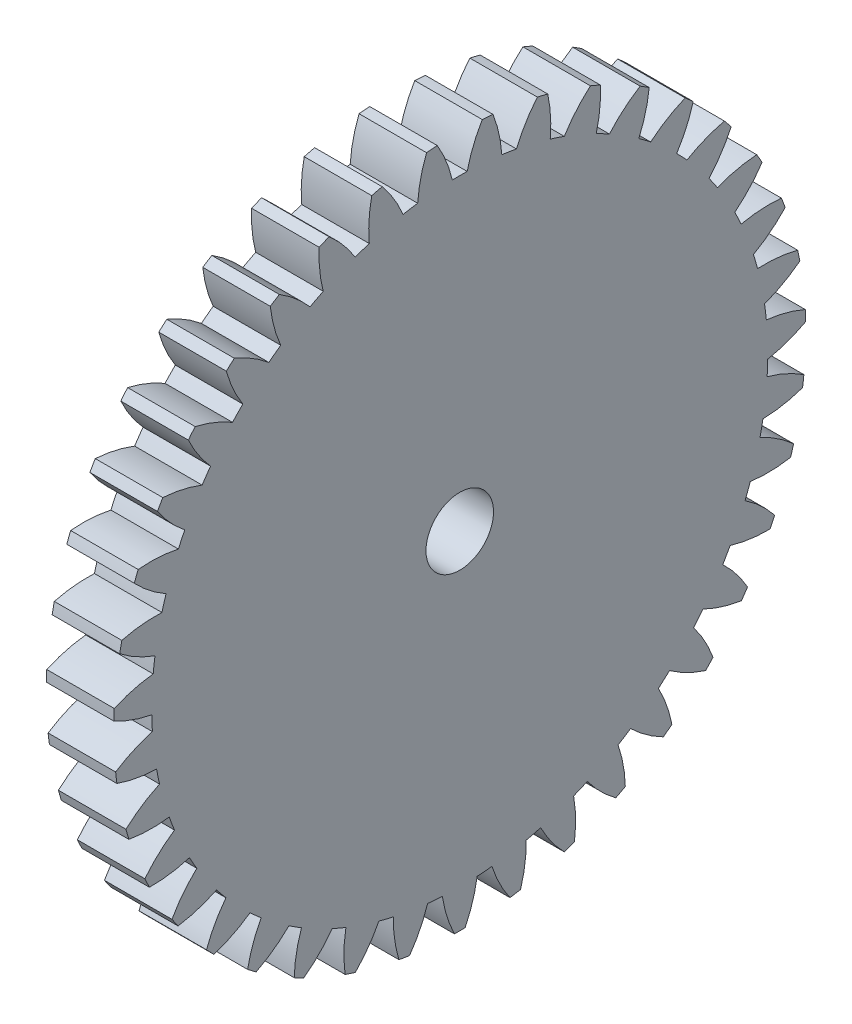
SolidWorks part; units mm, degrees
ref_plane "Plane1" through (0, 0, 0) normal (0, 0, 1) x (1, 0, 0)
ref_plane "Plane2" through (0, 0, 0) normal (0, 1, 0) x (1, 0, 0)
ref_plane "Plane3" through (0, 0, 0) normal (1, 0, 0) x (0, 0, -1)
sketch "HoldingSke" plane through (0, 0, 0) normal (0, 1, 0) x (1, 0, 0)
  line L0 (0, 0) -> (3.1086, -2.5173)
  line L1 (-15, 0) -> (100, 0) construction
  line L2 (0, 0) -> (-2.1039, 2.3779)
  line L3 (0, 0) -> (-11.863, 4.5341)
  line L4 (0, 0) -> (6.7114, 5.4348)
  line L5 (0, 0) -> (-46.8476, -17.4728)
  line L6 (0, 0) -> (-0.829, -0.5593)
  line L7 (-2.1039, 2.3779) -> (8.6586, 51.2059)
  line L8 (-76.2, 54.61) -> (-76.1, 54.61)
  line L9 (-71.009, 38.7566) -> (-53.1078, 45.2721)
  line L10 (-76.2, 71.12) -> (104.1128, 71.12)
  line L11 (0, 0) -> (-1, 0)
  line L12 (-76.2, 101.6) -> (-76.192, 101.6)
  line L13 (24.9733, 27.94) -> (52.9518, 28.4284)
  line L14 (24.9733, 27.94) -> (24.9743, 27.94)
  line L15 (24.9733, 27.94) -> (100.4006, 29.5858)
  line L16 (-63.627, -0.25) -> (-12.827, -0.25)
  circle A0 centre (0, 0) radius 0.5
  circle A1 centre (0, 0) radius 4.5615
  circle A2 centre (0, 0) radius 37.5
  circle A3 centre (0, 0) radius 0.5
  dimension "MHD" = 9.123
  dimension "Hub_dia" = 75
  dimension "Bore" = 1
  dimension "MBD" = 1
  dimension "Num_teeth" = 39
  dimension "Pitch" = 4
  dimension "Overall_len" = 50
  dimension "Show_teeth" = 39
  dimension "Thickness" = 1
  dimension "OAL" = 50.0001
  dimension "T_dim" = 0.1
  dimension "Ap" = 20
  dimension "H" = 19.05
  dimension "Pitch_radius" = 180.3128
  dimension "Width" = 1
  dimension "Backlash" = 0.008
  dimension "Addendum_fac" = 1
  dimension "Dedendum_fac" = 1.25
  dimension "Clearance_fac" = 0.25
  dimension "Dedendum_add" = 0.001
  dimension "Module" = 0.25
sketch "BasProSke" plane through (0, 0, 0) normal (0, 1, 0) x (1, 0, 0)
  line L0 (-10, 0) -> (60, 0) construction
  line L1 (0, 0) -> (0, 5.125)
  line L2 (0, 0) -> (1, 0)
  line L3 (1, 0) -> (1, 5.125)
  line L4 (1, 5.125) -> (0, 5.125)
  dimension "Thickness" = 1
  dimension "Diameter" = 10.25
revolve "Base-Revolve" add sketch "BasProSke" angle 360 about L0
sketch "TooCutSke" plane through (0, 0, 0) normal (1, 0, 0) x (0, 0, -1)
  line L1 (0, 0) -> (0, 107) construction
  line L2 (0, 0) -> (-0.2103, 4.8705) construction
  line L3 (0, 0) -> (-0.784, 9.7116) construction
  line L4 (-0.2103, 4.8705) -> (-0.392, 4.8558) construction
  arc A0 (0.1099, 4.5602) -> (-0.1099, 4.5602) centre (0, 0) ccw
  arc A1 (0.3479, 5.1386) -> (-0.3479, 5.1386) centre (0, 0) ccw
  circle A2 centre (0, 0) radius 4.875 construction
  circle A3 centre (0, 0) radius 4.581 construction
  arc A4 (-0.1099, 4.5602) -> (-0.3479, 5.1386) centre (-2.0089, 4.117) ccw
  arc A5 (0.3479, 5.1386) -> (0.1099, 4.5602) centre (2.0089, 4.117) ccw
  dimension "Root_dia" = 9.123
  dimension "Overcut_dia" = 10.3008
  dimension "Pitch_dia" = 9.75
  dimension "Base_dia" = 9.162
  dimension "Flank_rad" = 1.95
  dimension "Half_ang" = 4.615
  dimension "Half_CT" = 0.1823
extrude "ToothCut" cut sketch "TooCutSke" along normal through all
fillet "Breaks" [suppressed] radius 0.005
fillet "RootFillets" [suppressed] radius 0.0635
pattern_circular "TeethCuts" count 39 every 9.231 about axis through (-10, 0, 0) along (1, 0, 0) of "ToothCut", "RootFillets", "Breaks"
sketch "HubNeaOneSke" plane through (0, 0, 0) normal (-1, 0, 0) x (0, 0, 1)
  circle A0 centre (0, 0) radius 4.5615
  dimension "Diameter" = 9.123
extrude "HubNearOne" [suppressed] add sketch "HubNeaOneSke" along normal blind 49.0001
sketch "HubNeaBotSke" plane through (0, 0, 0) normal (-1, 0, 0) x (0, 0, 1)
  circle A0 centre (0, 0) radius 4.5615
  dimension "Diameter" = 9.123
extrude "HubNearBoth" [suppressed] add sketch "HubNeaBotSke" along normal blind 24.5
ref_plane "FarPln" through (1, 0, 0) normal (1, 0, 0) x (0, 0, -1)
sketch "HubFarSke" plane through (1, 0, 0) normal (1, 0, 0) x (0, 0, -1)
  circle A0 centre (0, 0) radius 4.5615
  dimension "Diameter" = 9.123
extrude "HubFar" [suppressed] add sketch "HubFarSke" along normal blind 24.5
sketch "BorSke" plane through (0, 0, 0) normal (1, 0, 0) x (0, 0, -1)
  circle A0 centre (0, 0) radius 0.5
  dimension "Diameter" = 1
extrude "Bore" cut sketch "BorSke" along normal mid plane 100.0001
sketch "KeySke" plane through (0, 0, 0) normal (1, 0, 0) x (0, 0, -1)
  line L0 (-0.05, 0) -> (-0.05, 0.6)
  line L1 (-0.05, 0.6) -> (0.05, 0.6)
  line L2 (0.05, 0.6) -> (0.05, 0)
  line L3 (0, 0) -> (0, 34) construction
  line L4 (-0.05, 0) -> (0.05, 0)
  dimension "Offset" = 0.6
extrude "Keyway" [suppressed] cut sketch "KeySke" along normal mid plane 100.0001
pattern_circular "Keyway2" [suppressed] count 2 every 90 about axis through (-10, 0, 0) along (1, 0, 0)
equation "' \"Module@HoldingSke\" = 6.35"
equation "' \"Num_teeth@HoldingSke\" = 12"
equation "' \"Ap@HoldingSke\" =  20"
equation "' \"Ap@HoldingSke\" = 20"
equation "' \"Width@HoldingSke\" = 0.5 * 25.4"
equation "' \"Hub_dia@HoldingSke\"= 1 * 25.4"
equation "' \"Hub_dia@HoldingSke\" = 1 * 25.4"
equation "' \"Overall_len@HoldingSke\" = 1.0 * 25.4"
equation "' \"Bore@HoldingSke\" = 0.75 * 25.4"
equation "' \"T_dim@HoldingSke\" = 0.1 * 25.4"
equation "' \"Width@KeySke\" = 0.25 * 25.4"
equation "' \"Show_teeth@HoldingSke\" = 13"
equation "' \"Backlash@HoldingSke\" = 0.009 * 25.4"
equation "' \"Addendum_fac@HoldingSke\" = 1.0"
equation "' \"Dedendum_fac@HoldingSke\" = 1.25"
equation "' \"Dedendum_add@HoldingSke\" = 0.00005 * 25.4"
equation "' \"Clearance_fac@HoldingSke\" = 0.25"
equation "\"Pitch@HoldingSke\" = 1 / \"Module@HoldingSke\""
equation "\"Overcut_dia@TooCutSke\" = (\"Num_teeth@HoldingSke\" + 2 * \"Addendum_fac@HoldingSke\") / \"Pitch@HoldingSke\" + 0.002 * 25.4"
equation "\"Pitch_dia@TooCutSke\" = \"Num_teeth@HoldingSke\" / \"Pitch@HoldingSke\""
equation "\"Base_dia@TooCutSke\" = \"Num_teeth@HoldingSke\" / \"Pitch@HoldingSke\" * cos((\"Ap@HoldingSke\"  * 3.14159265 / 180))"
equation "\"Root_dia@TooCutSke\" = (\"Num_teeth@HoldingSke\" + 2) / \"Pitch@HoldingSke\" - 2 * (\"Addendum_fac@HoldingSke\" + \"Dedendum_fac@HoldingSke\") / \"Pitch@HoldingSke\" - \"Dedendum_add@HoldingSke\" * 2"
equation "\"Half_ang@TooCutSke\" = 180 / \"Num_teeth@HoldingSke\""
equation "\"Half_CT@TooCutSke\" = \"Num_teeth@HoldingSke\" / \"Pitch@HoldingSke\" * sin((3.14159265 / 2 / \"Num_teeth@HoldingSke\")) / 2 - 7 * \"Backlash@HoldingSke\" / 4"
equation "\"Flank_rad@TooCutSke\" = \"Num_teeth@HoldingSke\" / \"Pitch@HoldingSke\" / 5"
equation "\"Radius@RootFillets\" = \"Clearance_fac@HoldingSke\" / \"Pitch@HoldingSke\" + \"Dedendum_add@HoldingSke\""
equation "\"Break_rad@Breaks\" = 0.02 / \"Pitch@HoldingSke\""
equation "\"Thickness@HoldingSke\" = \"Width@HoldingSke\""
equation "\"OAL@HoldingSke\" = \"Thickness@HoldingSke\""
equation "\"MHD@HoldingSke\" = (\"Num_teeth@HoldingSke\" + 2) / \"Pitch@HoldingSke\" - 2 * (\"Addendum_fac@HoldingSke\" + \"Dedendum_fac@HoldingSke\")  / \"Pitch@HoldingSke\" - \"Dedendum_add@HoldingSke\" * 2"
equation "\"MBD@HoldingSke\" = (\"Num_teeth@HoldingSke\" + 2) / \"Pitch@HoldingSke\" - 2 * (\"Addendum_fac@HoldingSke\" + \"Dedendum_fac@HoldingSke\")  / \"Pitch@HoldingSke\" - \"Dedendum_add@HoldingSke\" * 2 - 0.002 * 25.4"
equation "\"MHD@HoldingSke\" = ((sgn( \"MHD@HoldingSke\" - \"Hub_dia@HoldingSke\" )-1)*( \"MHD@HoldingSke\" - \"Hub_dia@HoldingSke\" ))/-2+ \"Hub_dia@HoldingSke\""
equation "\"MBD@HoldingSke\" = ((sgn( \"MBD@HoldingSke\" - \"Bore@HoldingSke\" )-1)*( \"MBD@HoldingSke\" - \"Bore@HoldingSke\" ))/-2+ \"Bore@HoldingSke\""
equation "\"OAL@HoldingSke\" = ((sgn( \"OAL@HoldingSke\" - \"Overall_len@HoldingSke\" )+1)*( \"OAL@HoldingSke\" - \"Overall_len@HoldingSke\" ))/2 + \"Overall_len@HoldingSke\" + 0.000002 * 25.4"
equation "\"Num_teeth@TeethCuts\" = int( \"Show_teeth@HoldingSke\" ) + 1"
equation "\"Num_teeth@TeethCuts\" = ((sgn( \"Num_teeth@TeethCuts\" - \"Num_teeth@HoldingSke\" )-1)*( \"Num_teeth@TeethCuts\" - \"Num_teeth@HoldingSke\" ))/-2+ \"Num_teeth@HoldingSke\""
equation "\"Num_teeth@TeethCuts\" = ((sgn( \"Num_teeth@TeethCuts\" - 2.0)+1)*( \"Num_teeth@TeethCuts\" - 2.0))/2 +2.0"
equation "\"Angle@TeethCuts\" = 360.0 / \"Num_teeth@HoldingSke\""
equation "\"Diameter@BasProSke\" = (\"Num_teeth@HoldingSke\" + 2 * \"Addendum_fac@HoldingSke\") / \"Pitch@HoldingSke\""
equation "\"Thickness@BasProSke\"  = \"Thickness@HoldingSke\""
equation "' \"Fillet_rad@BasProSke\" =  \"Thickness@HoldingSke\" * 0.05"
equation "' \"Fillet_rad@BasProSke\" = \"Thickness@HoldingSke\" * 0.05"
equation "\"MHD@HoldingSke\" = ((sgn( \"MHD@HoldingSke\" - \"Root_dia@TooCutSke\" )-1)*( \"MHD@HoldingSke\" - \"Root_dia@TooCutSke\" ))/-2+ \"Root_dia@TooCutSke\""
equation "\"Diameter@HubNeaOneSke\" = \"MHD@HoldingSke\""
equation "\"Length@HubNearOne\" = \"OAL@HoldingSke\" - \"Thickness@BasProSke\""
equation "\"Diameter@HubNeaBotSke\" = \"MHD@HoldingSke\""
equation "\"Length@HubNearBoth\" = ( \"OAL@HoldingSke\" - \"Thickness@BasProSke\" ) / 2.0"
equation "\"Thickness@FarPln\" = \"Thickness@BasProSke\""
equation "\"Diameter@HubFarSke\" = \"MHD@HoldingSke\""
equation "\"Length@HubFar\" = ( \"OAL@HoldingSke\" - \"Thickness@BasProSke\" ) / 2.0"
equation "\"Diameter@BorSke\" = \"MBD@HoldingSke\""
equation "\"D1@Bore\" = \"OAL@HoldingSke\" * 2.0"
equation "\"D1@Keyway\" = \"OAL@HoldingSke\" * 2.0"
equation "\"Offset@KeySke\" = \"T_dim@HoldingSke\" + \"MBD@HoldingSke\" / 2.0"
